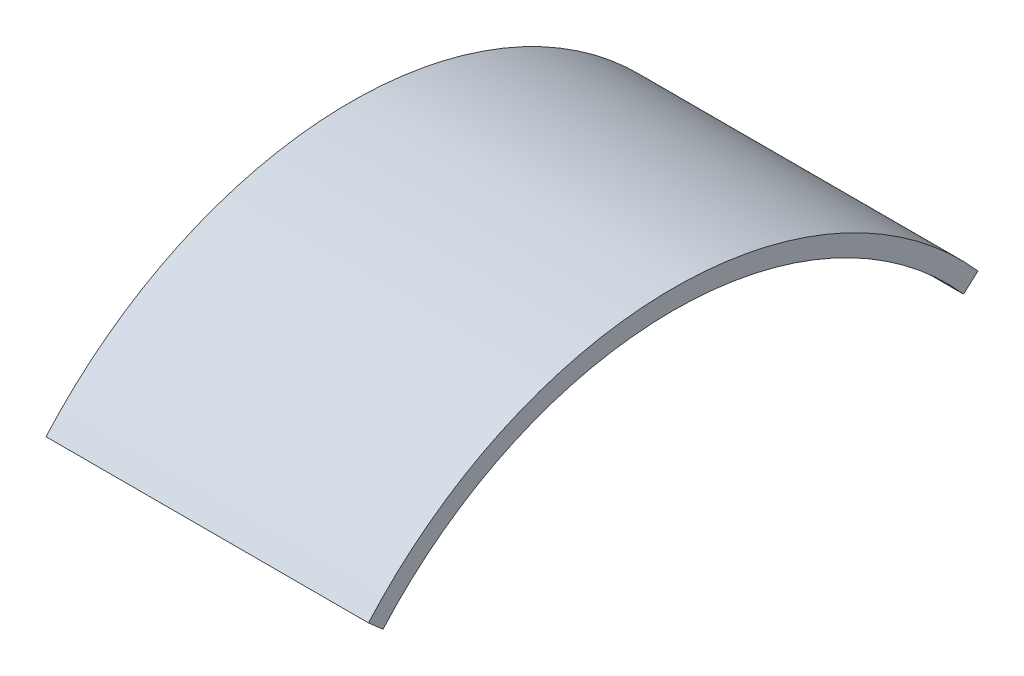
SolidWorks part; units mm, degrees
ref_plane "Front Plane" through (0, 0, 0) normal (0, 0, 1) x (1, 0, 0)
ref_plane "Top Plane" through (0, 0, 0) normal (0, 1, 0) x (1, 0, 0)
ref_plane "Right Plane" through (0, 0, 0) normal (1, 0, 0) x (0, 0, -1)
sketch "Sketch1" plane through (0, 0, 0) normal (1, 0, 0) x (0, 0, -1)
  line L0 (-45, 39.6863) -> (-47.25, 41.6706)
  line L1 (-45, 39.6863) -> (0, 0) construction
  line L2 (0, 0) -> (45, 39.6863) construction
  line L3 (45, 39.6863) -> (47.25, 41.6706)
  line L4 (0, 63) -> (0, 0) construction
  arc A0 (-45, 39.6863) -> (45, 39.6863) centre (0, 0) cw
  arc A1 (-47.25, 41.6706) -> (47.25, 41.6706) centre (0, 0) cw
  dimension "D1" = 60
  dimension "D2" = 63
  dimension "D3" = 90
extrude "Boss-Extrude1" add sketch "Sketch1" along normal blind 50
